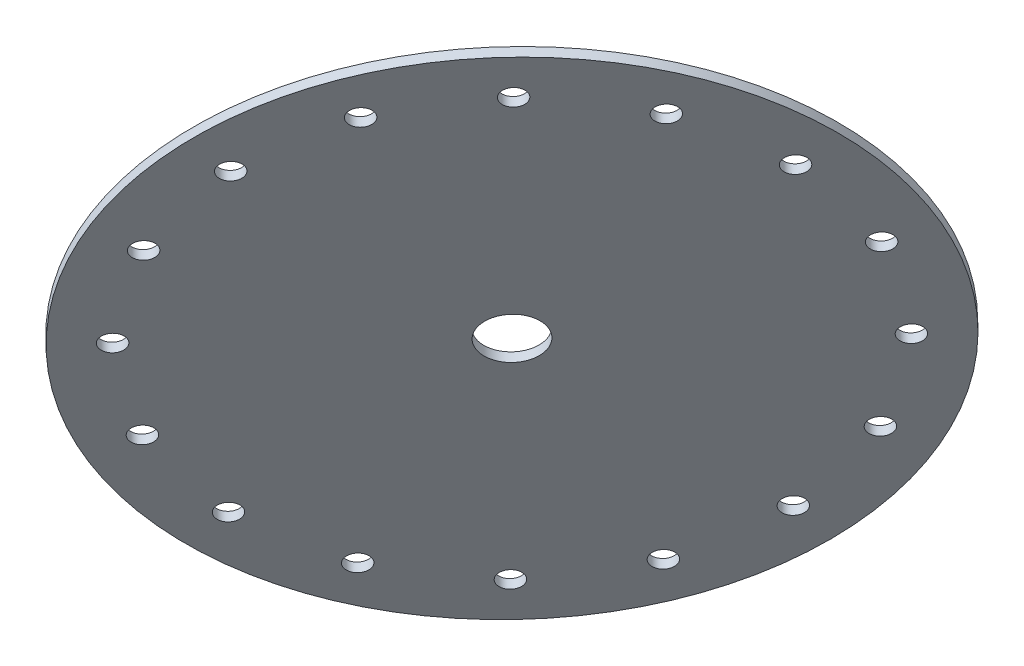
SolidWorks part; units mm, degrees
ref_plane "Front Plane" through (0, 0, 0) normal (0, 0, 1) x (1, 0, 0)
ref_plane "Top Plane" through (0, 0, 0) normal (0, 1, 0) x (1, 0, 0)
ref_plane "Right Plane" through (0, 0, 0) normal (1, 0, 0) x (0, 0, -1)
sketch "Sketch2" plane through (-290.961, 128.347, -280.4019) normal (0.6863, -0.3027, 0.6614) x (0.6169, -0.2394, -0.7497)
  circle A0 centre (0, 0) radius 175
  circle A1 centre (0, 0) radius 15
  circle A2 centre (-75.8119, -129.4317) radius 6.1
  circle A3 centre (-119.5724, -90.5673) radius 6.1
  circle A4 centre (-145.1291, -37.9149) radius 6.1
  circle A5 centre (-148.5912, 20.5097) radius 6.1
  circle A6 centre (-129.4317, 75.8119) radius 6.1
  circle A7 centre (-90.5673, 119.5724) radius 6.1
  circle A8 centre (-37.9149, 145.1291) radius 6.1
  circle A9 centre (20.5097, 148.5912) radius 6.1
  circle A10 centre (75.8119, 129.4317) radius 6.1
  circle A11 centre (119.5724, 90.5673) radius 6.1
  circle A12 centre (145.1291, 37.9149) radius 6.1
  circle A13 centre (148.5912, -20.5097) radius 6.1
  circle A14 centre (129.4317, -75.8119) radius 6.1
  circle A15 centre (90.5673, -119.5724) radius 6.1
  circle A16 centre (37.9149, -145.1291) radius 6.1
  circle A17 centre (-20.5097, -148.5912) radius 6.1
  point P39 (0, 0)
  dimension "D1" = 350
  dimension "D2" = 30
  dimension "D3" = 12.2
  dimension "D5" = 150
  dimension "D4" = 16
extrude "Boss-Extrude1" add sketch "Sketch2" along normal blind 5
